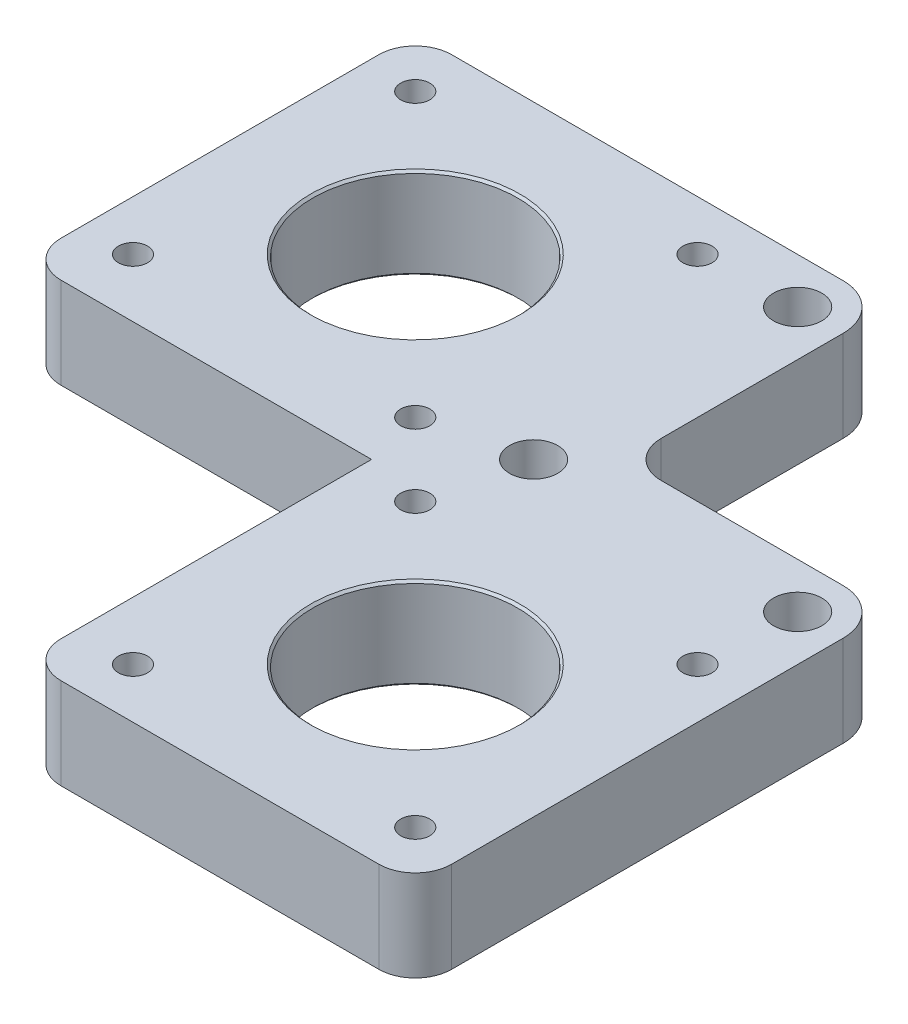
SolidWorks part; units mm, degrees
material "AISI 1045 Steel, cold drawn"
ref_plane "Front Plane" through (0, 0, 0) normal (0, 0, 1) x (1, 0, 0)
ref_plane "Top Plane" through (0, 0, 0) normal (0, 1, 0) x (1, 0, 0)
ref_plane "Right Plane" through (0, 0, 0) normal (1, 0, 0) x (0, 0, -1)
sketch "Sketch1" plane through (0, 0, 0) normal (0, 1, 0) x (1, 0, 0)
  line L1 (60, -21) -> (18, -21) construction
  line L2 (60, -21) -> (60, 21) construction
  line L3 (60, 21) -> (18, 21) construction
  line L4 (18, -21) -> (18, 21) construction
  line L5 (60, -21) -> (18, 21) construction
  line L6 (60, 21) -> (18, -21) construction
  line L7 (21, 18) -> (-21, 18) construction
  line L8 (21, 18) -> (21, 60) construction
  line L9 (21, 60) -> (-21, 60) construction
  line L10 (-21, 18) -> (-21, 60) construction
  line L11 (21, 18) -> (-21, 60) construction
  line L12 (21, 60) -> (-21, 18) construction
  line L14 (60, -21) -> (60, 31)
  line L15 (60, 31) -> (31, 31)
  line L16 (31, 31) -> (31, 60)
  line L17 (31, 60) -> (-21, 60)
  line L18 (-21, 60) -> (-21, 18)
  line L19 (-21, 18) -> (18, 18)
  line L20 (18, 18) -> (18, -21)
  line L21 (18, -21) -> (60, -21)
  point P0 (39, 0)
  point P5 (0, 39)
  dimension "D1" = 42
  dimension "D2" = 39
  dimension "D3" = 39
  dimension "D4" = 10
  dimension "D5" = 10
extrude "Boss-Extrude1" add sketch "Sketch1" along normal blind 10
hole_wizard "Ø22.5 (22.5) Diameter Hole1" positions "Sketch5" profile "Sketch7" hole size "Ø22.5" standard "ANSI Metric" end condition through all
sketch "Sketch5" plane through (0, 10, 0) normal (0, 1, 0) x (1, 0, 0)
  point P0 (0, 39)
  point P3 (39, 0)
sketch "Sketch7" plane through (0, 10, -39) normal (1, 0, 0) x (0, 0, 1)
  line L0 (0, 0) -> (0, 10)
  line L1 (0, 10) -> (11.25, 10)
  line L2 (11.25, 10) -> (11.25, 0)
  line L5 (11.25, 0) -> (0, 0)
  line L11 (0, -6.35) -> (0, 107.95) construction
  dimension "Thru Hole Dia." = 22.5
  dimension "Thru Hole Depth" = 10
sketch "Sketch8" plane through (0, 0, 0) normal (0, 1, 0) x (1, 0, 0)
  line L0 (21, 60) -> (-21, 18) construction
  line L1 (15.5, 23.5) -> (-15.5, 23.5)
  line L2 (15.5, 23.5) -> (15.5, 54.5)
  line L3 (15.5, 54.5) -> (-15.5, 54.5)
  line L4 (-15.5, 23.5) -> (-15.5, 54.5)
  line L5 (15.5, 23.5) -> (-15.5, 54.5) construction
  line L6 (15.5, 54.5) -> (-15.5, 23.5) construction
  line L7 (21, 18) -> (-21, 60) construction
  line L8 (60, 21) -> (18, -21) construction
  line L9 (23.5, -15.5) -> (54.5, -15.5)
  line L10 (23.5, -15.5) -> (23.5, 15.5)
  line L11 (23.5, 15.5) -> (54.5, 15.5)
  line L12 (54.5, -15.5) -> (54.5, 15.5)
  line L13 (23.5, -15.5) -> (54.5, 15.5) construction
  line L14 (23.5, 15.5) -> (54.5, -15.5) construction
  point P0 (0, 39)
  point P9 (39, 0)
  dimension "D1" = 31
hole_wizard "CBORE for M3 SHCS1" positions "Sketch9" profile "Sketch10" counterbore size "M3" standard "ANSI Metric" end condition through all
sketch "Sketch9" plane through (0, 0, 0) normal (0, -1, 0) x (-1, 0, 0)
  point P0 (-54.5, 15.5)
  point P3 (-23.5, 15.5)
  point P6 (-23.5, -15.5)
  point P9 (-54.5, -15.5)
  point P12 (-15.5, 54.5)
  point P15 (-15.5, 23.5)
  point P18 (15.5, 23.5)
  point P21 (15.5, 54.5)
sketch "Sketch10" plane through (54.5, 0, -15.5) normal (1, 0, 0) x (0, 0, -1)
  line L0 (0, 0) -> (0, 10)
  line L1 (0, 10) -> (1.6, 10)
  line L3 (1.6, 10) -> (1.6, 3)
  line L4 (1.6, 3) -> (3.25, 3)
  line L5 (3.25, 3) -> (3.25, 0)
  line L7 (3.25, 0) -> (0, 0)
  line L11 (0, -6.35) -> (0, 107.95) construction
  dimension "Thru Hole Dia." = 3.2
  dimension "Thru Hole Depth" = 10
  dimension "C'Bore Dia." = 6.5
  dimension "C'Bore Depth" = 3
hole_wizard "M5 Clearance Hole1" positions "Sketch11" profile "Sketch12" hole size "M5" standard "ANSI Metric" end condition through all
sketch "Sketch11" plane through (0, 10, 0) normal (0, 1, 0) x (1, 0, 0)
  line L0 (55, 26) -> (26, 26) construction
  line L1 (26, 26) -> (26, 55) construction
  line L3 (31, 31) -> (31, 60) construction
  line L4 (31, 60) -> (-21, 60) construction
  line L5 (60, -21) -> (60, 31) construction
  line L6 (60, 31) -> (31, 31) construction
  point P0 (26, 55)
  point P2 (26, 26)
  point P4 (55, 26)
  dimension "D1" = 5
  dimension "D2" = 5
  dimension "D3" = 5
  dimension "D4" = 5
sketch "Sketch12" plane through (26, 10, -55) normal (1, 0, 0) x (0, 0, 1)
  line L0 (0, 0) -> (0, 10)
  line L1 (0, 10) -> (2.65, 10)
  line L2 (2.65, 10) -> (2.65, 0)
  line L5 (2.65, 0) -> (0, 0)
  line L11 (0, -6.35) -> (0, 107.95) construction
  dimension "Thru Hole Dia." = 5.3
  dimension "Thru Hole Depth" = 10
hole_wizard "Tap Drill for M5x0.8 Tap1" positions "Sketch13" profile "Sketch15" hole size "M5x0.8" standard "ANSI Metric"
sketch "Sketch13" plane through (0, 0, -18) normal (0, 0, 1) x (1, 0, 0)
  line L3 (-21, 10) -> (-21, 0) construction
  point P0 (5, 5)
  point P2 (-8.75, 5)
  point P22 (-21, 5)
  dimension "D1" = 8.75
  dimension "D2" = 5
sketch "Sketch15" plane through (5, 5, -18) normal (1, 0, 0) x (0, -1, 0)
  line L0 (0, 0) -> (0, 9.2618)
  line L1 (0, 9.2618) -> (2.1, 8)
  line L2 (2.1, 8) -> (2.1, 0)
  line L5 (2.1, 0) -> (0, 0)
  line L10 (0, 9.2618) -> (-2.1, 8) construction
  line L11 (0, -6.35) -> (0, 107.95) construction
  dimension "Hole Dia." = 4.2
  dimension "Hole Depth" = 8
  dimension "Drill Angle" = 118
ref_plane "Plane1" through (0, 0, 0) normal (0.7071, 0, 0.7071) x (0.7071, 0, -0.7071)
mirror "Mirror1" about plane through (0, 0, 0) normal (0.7071, 0, 0.7071) of "Tap Drill for M5x0.8 Tap1"
sketch "Sketch16" plane through (0, 10, 0) normal (0, 1, 0) x (1, 0, 0)
  line L1 (17.1, 17.1) -> (-21, 17.1)
  line L2 (17.1, 17.1) -> (17.1, -21)
  line L6 (-21, 17.1) -> (-21, 18)
  line L7 (-21, 18) -> (18, 18)
  line L8 (18, 18) -> (18, -21)
  line L9 (18, -21) -> (17.1, -21)
  circle A0 centre (39, 0) radius 11.25 construction
  dimension "D1" = 21.9
extrude "Boss-Extrude2" add sketch "Sketch16" against normal up to surface (10 mm away) up to face at (26, 0, -52.35)
fillet "Fillet2" radius 4 5 edges at (-21, 5, -60) (31, 5, -31) (60, 5, 21) (17.1, 5, 21) (-21, 5, -17.1)
fillet "Fillet3" radius 5 2 edges at (60, 5, -31) (31, 5, -60)
chamfer "Chamfer1" distance 0.25 angle 45 4 edges at (39, 10, 11.25) (39, 0, 11.25) (0, 10, -27.75) (0, 0, -27.75)
